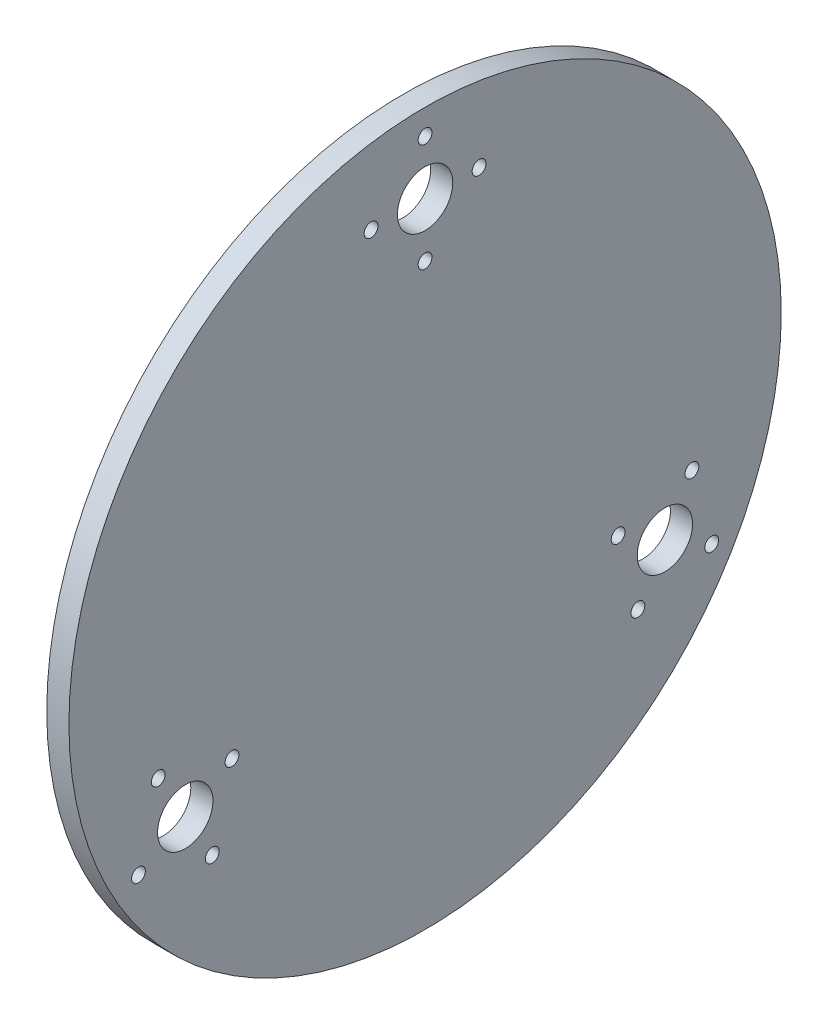
SolidWorks part; units mm, degrees
ref_plane "Front Plane" through (0, 0, 0) normal (0, 0, 1) x (1, 0, 0)
ref_plane "Top Plane" through (0, 0, 0) normal (0, 1, 0) x (1, 0, 0)
ref_plane "Right Plane" through (0, 0, 0) normal (1, 0, 0) x (0, 0, -1)
sketch "Sketch1" plane through (0, 0, 0) normal (1, 0, 0) x (0, 0, -1)
  line L0 (-72.7, 0) -> (72.7, 0) construction
  line L1 (-9.75, 50) -> (9.75, 50) construction
  line L2 (0, 40.25) -> (0, 59.75) construction
  circle A0 centre (51.745, -29.875) radius 1.25
  circle A1 centre (0, 50) radius 5
  circle A2 centre (48.1763, -16.5563) radius 1.25
  circle A3 centre (43.3013, -25) radius 5
  circle A4 centre (0, 0) radius 64.3086
  circle A5 centre (0, 59.75) radius 1.25
  circle A6 centre (9.75, 50) radius 1.25
  circle A7 centre (0, 40.25) radius 1.25
  circle A8 centre (-9.75, 50) radius 1.25
  circle A9 centre (38.4263, -33.4437) radius 1.25
  circle A10 centre (34.8575, -20.125) radius 1.25
  circle A11 centre (-51.745, -29.875) radius 1.25
  circle A12 centre (-38.4263, -33.4437) radius 1.25
  circle A13 centre (-43.3013, -25) radius 5
  circle A14 centre (-48.1763, -16.5563) radius 1.25
  circle A15 centre (-34.8575, -20.125) radius 1.25
  point P11 (0, 0)
  point P24 (0, 48.85)
  point P39 (0, 0)
  dimension "D1" = 50
  dimension "D3" = 19.5
  dimension "D4" = 10
  dimension "D5" = 2.5
  dimension "D2" = 3
extrude "Boss-Extrude2" add sketch "Sketch1" along normal blind 4
